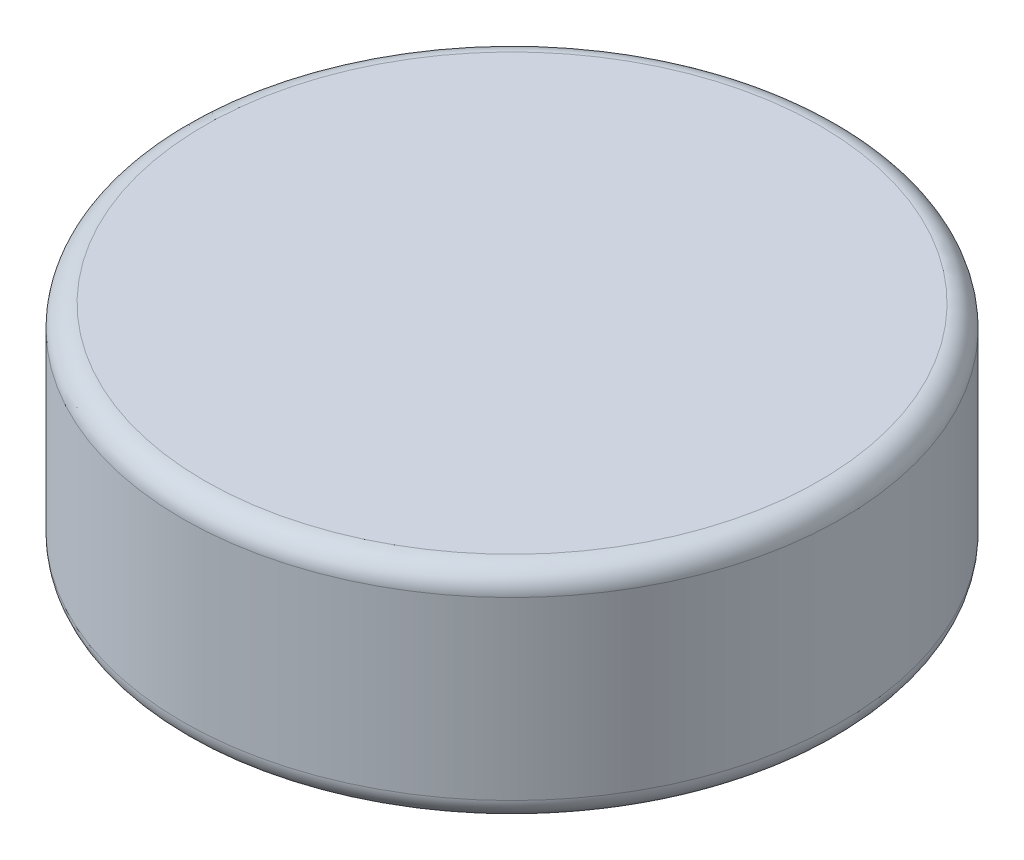
SolidWorks part; units mm, degrees
ref_plane "Front Plane" through (0, 0, 0) normal (0, 0, 1) x (1, 0, 0)
ref_plane "Top Plane" through (0, 0, 0) normal (0, 1, 0) x (1, 0, 0)
ref_plane "Right Plane" through (0, 0, 0) normal (1, 0, 0) x (0, 0, -1)
sketch "Sketch1" plane through (0, 0, 0) normal (0, 1, 0) x (1, 0, 0)
  circle A0 centre (0, 0) radius 1.5
  dimension "D1" = 3
extrude "Boss-Extrude1" add sketch "Sketch1" along normal blind 1
fillet "Fillet1" radius 0.1 2 edges at (0, 0, 1.5) (0, 1, 1.5)
